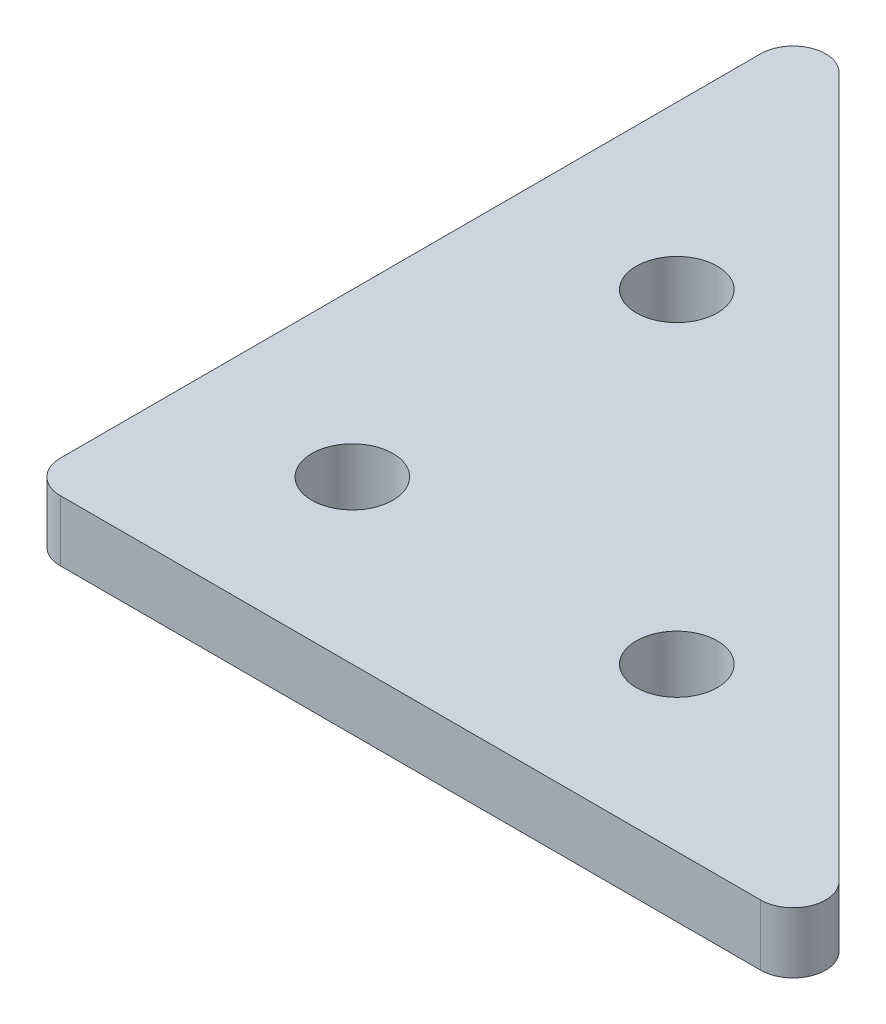
SolidWorks part; units mm, degrees
material "1060 Alloy"
ref_plane "Front Plane" through (0, 0, 0) normal (0, 0, 1) x (1, 0, 0)
ref_plane "Top Plane" through (0, 0, 0) normal (0, 1, 0) x (1, 0, 0)
ref_plane "Right Plane" through (0, 0, 0) normal (1, 0, 0) x (0, 0, -1)
sketch "Sketch1" plane through (0, 0, 0) normal (0, 1, 0) x (1, 0, 0)
  line L0 (-431.938, -442.7006) -> (-377.1101, -442.7006)
  line L1 (-431.938, -442.7006) -> (-335.418, -442.7006) construction
  line L2 (-434.478, -440.1606) -> (-434.478, -385.3327)
  line L3 (-434.478, -343.6406) -> (-434.478, -440.1606) construction
  line L4 (-430.142, -383.5367) -> (-375.3141, -438.3646)
  arc A0 (-434.478, -385.3327) -> (-430.142, -383.5367) centre (-431.938, -385.3327) cw
  arc A1 (-375.3141, -438.3646) -> (-377.1101, -442.7006) centre (-377.1101, -440.1606) cw
  arc A2 (-434.478, -440.1606) -> (-431.938, -442.7006) centre (-431.938, -440.1606) ccw
  point P10 (-434.478, -379.2006)
  point P13 (-370.978, -442.7006)
  point P16 (-434.478, -442.7006)
  dimension "D1" = 2.54
  dimension "D2" = 2.54
  dimension "D3" = 2.54
extrude "Boss-Extrude1" add sketch "Sketch1" along normal blind 4.7625
sketch "Sketch2" plane through (0, 4.7625, 0) normal (0, 1, 0) x (1, 0, 0)
  line L0 (-421.778, -404.6006) -> (-421.778, -430.0006) construction
  line L1 (-421.778, -430.0006) -> (-396.378, -430.0006) construction
hole_wizard "1/4 (0.25) Diameter Hole1" positions "Sketch3" profile "Sketch4" hole size "1/4" standard "ANSI Inch" end condition through all
sketch "Sketch3" plane through (0, 4.7625, 0) normal (0, 1, 0) x (1, 0, 0)
  point P0 (-421.778, -404.6006)
  point P3 (-421.778, -430.0006)
  point P6 (-396.378, -430.0006)
sketch "Sketch4" plane through (-421.778, 4.7625, 404.6006) normal (1, 0, 0) x (0, 0, 1)
  line L0 (0, 0) -> (0, 4.7625)
  line L1 (0, 4.7625) -> (3.175, 4.7625)
  line L2 (3.175, 4.7625) -> (3.175, 0)
  line L5 (3.175, 0) -> (0, 0)
  line L11 (0, -6.35) -> (0, 107.95) construction
  dimension "Thru Hole Dia." = 6.35
  dimension "Thru Hole Depth" = 4.7625
